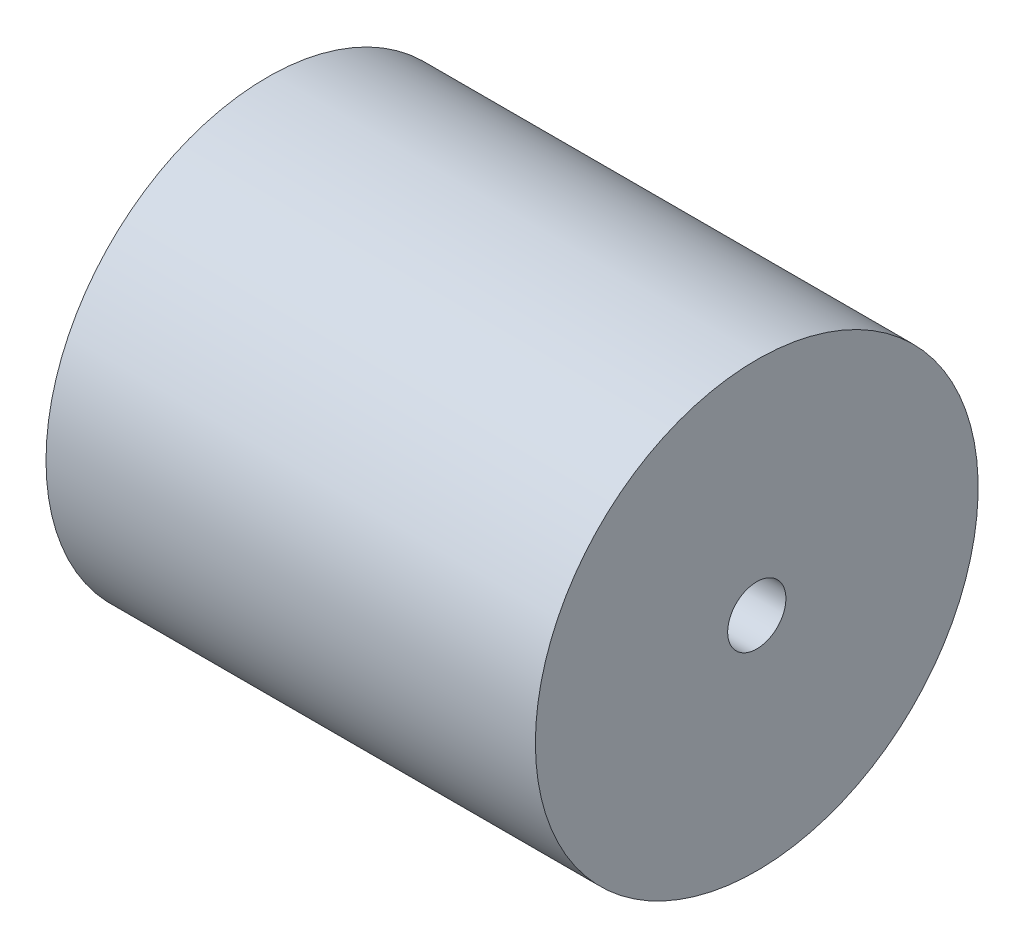
SolidWorks part; units mm, degrees
ref_plane "Front Plane" through (0, 0, 0) normal (0, 0, 1) x (1, 0, 0)
ref_plane "Top Plane" through (0, 0, 0) normal (0, 1, 0) x (1, 0, 0)
ref_plane "Right Plane" through (0, 0, 0) normal (1, 0, 0) x (0, 0, -1)
sketch "Sketch1" plane through (0, 0, 0) normal (1, 0, 0) x (0, 0, -1)
  circle A0 centre (0, 0) radius 9.5
  circle A1 centre (0, 0) radius 1.25
  dimension "D1" = 19
  dimension "D2" = 2.5
extrude "Boss-Extrude1" add sketch "Sketch1" along normal blind 21
